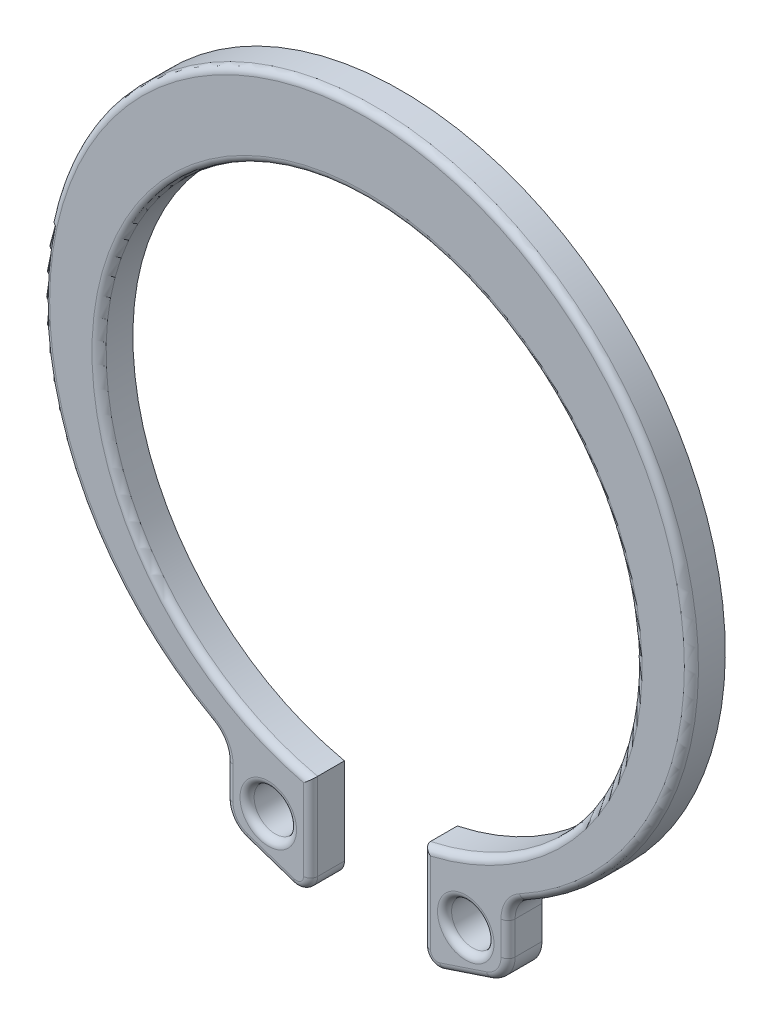
SolidWorks part; units mm, degrees
material "AISI Type A2 Tool Steel"
ref_plane "Front Plane" through (0, 0, 0) normal (0, 0, 1) x (1, 0, 0)
ref_plane "Top Plane" through (0, 0, 0) normal (0, 1, 0) x (1, 0, 0)
ref_plane "Right Plane" through (0, 0, 0) normal (1, 0, 0) x (0, 0, -1)
sketch "Sketch1" plane through (0, 0, 0) normal (0, 0, 1) x (1, 0, 0)
  line L0 (-20.0763, 0) -> (22.6413, 0) construction
  line L1 (0, 14.6503) -> (0, -16.6234) construction
  line L2 (-2, -9.2871) -> (-2, -10.5248)
  line L3 (2, -9.2871) -> (2, -10.5248)
  line L4 (-2, -10.5248) -> (-2, -12.3624)
  line L5 (-2.6581, -12.8368) -> (-4.3162, -12.2841)
  line L6 (-5, -11.3354) -> (-5, -10.1659)
  line L7 (5, -11.3354) -> (5, -10.1659)
  line L8 (2.6581, -12.8368) -> (4.3162, -12.2841)
  line L9 (2, -10.5248) -> (2, -12.3624)
  arc A0 (2, -9.2871) -> (-2, -9.2871) centre (0, 0) ccw
  circle A2 centre (-3.5, -11.0562) radius 0.7516
  circle A3 centre (3.5, -11.0562) radius 0.7516
  arc A4 (5.52, -9.2886) -> (-5.52, -9.2886) centre (0, 0.8) ccw
  arc A5 (-5, -10.1659) -> (-5.52, -9.2886) centre (-6, -10.1659) ccw
  arc A6 (5, -10.1659) -> (5.52, -9.2886) centre (6, -10.1659) cw
  arc A7 (5, -11.3354) -> (4.3162, -12.2841) centre (4, -11.3354) cw
  arc A8 (-4.3162, -12.2841) -> (-5, -11.3354) centre (-4, -11.3354) cw
  arc A9 (2.6581, -12.8368) -> (2, -12.3624) centre (2.5, -12.3624) cw
  arc A10 (-2, -12.3624) -> (-2.6581, -12.8368) centre (-2.5, -12.3624) cw
  point P24 (-5, -9.5562)
  point P27 (5, -9.5562)
  point P30 (5, -12.0562)
  point P33 (-5, -12.0562)
  point P36 (2, -13.0562)
  point P39 (-2, -13.0562)
  dimension "D1" = 19
  dimension "D2" = 1
  dimension "D9" = 1.5033
  dimension "D5" = 0.5
  dimension "D3" = 0.8
  dimension "D4" = 4
  dimension "D6" = 3
  dimension "D7" = 1
  dimension "D8" = 2.5
  dimension "D10" = 1.5
  dimension "D11" = 1
extrude "Boss-Extrude1" add sketch "Sketch1" along normal blind 1.2
fillet "Fillet1" radius 0.25 16 edges at (2.7484, -11.0562, 1.2) (0, 12.3, 1.2) (5.1398, -9.656, 1.2) (5, -10.7506, 1.2) (4.8112, -11.9201, 1.2) (3.4872, -12.5604, 1.2) (2.2076, -12.7681, 1.2) (2, -10.8248, 1.2) (0, 9.5, 1.2) (-2, -10.8248, 1.2) (-2.2076, -12.7681, 1.2) (-3.4872, -12.5604, 1.2) (-4.8112, -11.9201, 1.2) (-5, -10.7506, 1.2) (-5.1398, -9.656, 1.2) (-2.7484, -11.0562, 1.2)
